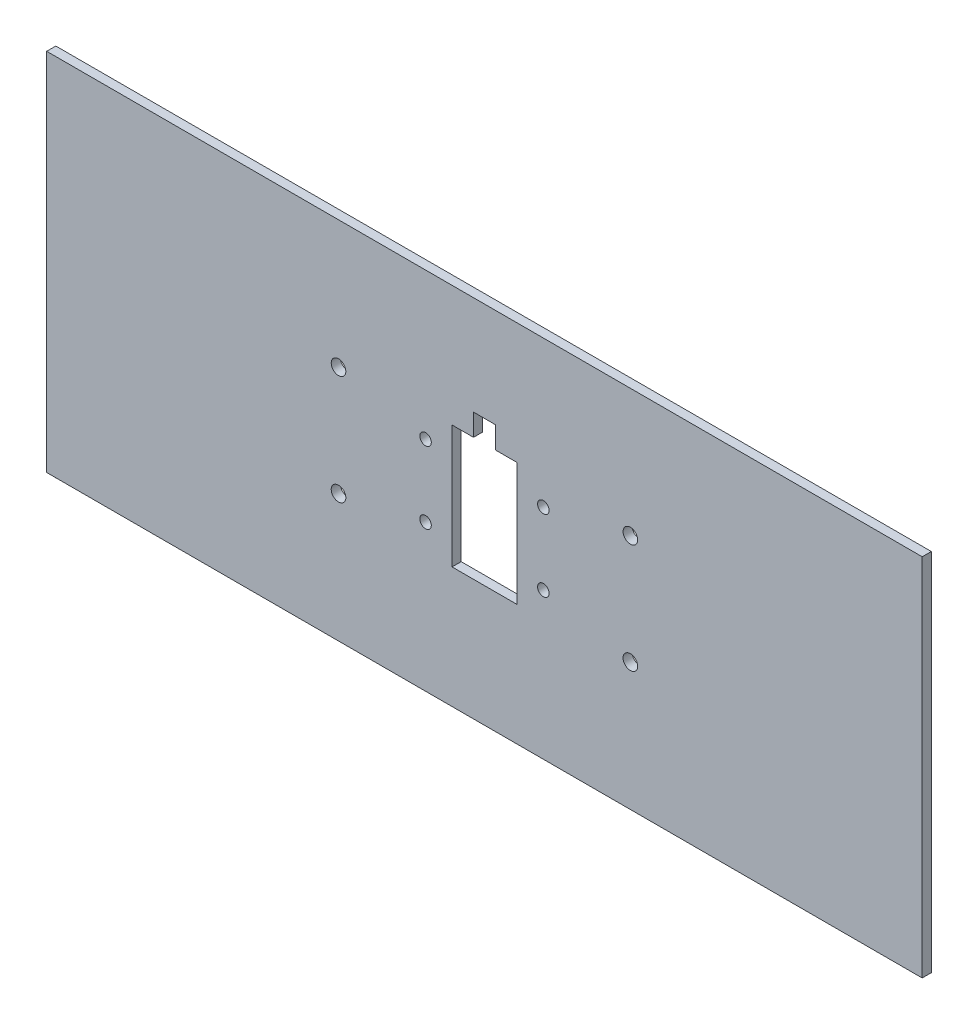
SolidWorks part; units mm, degrees
ref_plane "Front Plane" through (0, 0, 0) normal (0, 0, 1) x (1, 0, 0)
ref_plane "Top Plane" through (0, 0, 0) normal (0, 1, 0) x (1, 0, 0)
ref_plane "Right Plane" through (0, 0, 0) normal (1, 0, 0) x (0, 0, -1)
sketch "Sketch1" plane through (0, 0, 0) normal (0, 0, 1) x (1, 0, 0)
  line L0 (-152.4, 63.5) -> (152.4, -63.5) construction
  line L1 (-152.4, -63.5) -> (152.4, -63.5)
  line L2 (-152.4, -63.5) -> (-152.4, 63.5)
  line L3 (-152.4, 63.5) -> (152.4, 63.5)
  line L4 (152.4, -63.5) -> (152.4, 63.5)
  line L9 (-152.4, -63.5) -> (152.4, 63.5) construction
  point P4 (0, 0)
  dimension "D1" = 304.8
  dimension "D2" = 127
extrude "Boss-Extrude1" add sketch "Sketch1" along normal blind 3.175
sketch "Sketch2" plane through (0, 0, 3.175) normal (0, 0, 1) x (1, 0, 0)
  line L2 (50.8, 19.05) -> (-50.8, -19.05) construction
  line L3 (50.8, -19.05) -> (-50.8, 19.05) construction
  line L4 (50.8, 19.05) -> (-50.8, 19.05) construction
  line L5 (50.8, -19.05) -> (50.8, 19.05) construction
  circle A0 centre (50.8, 19.05) radius 2.54
  circle A1 centre (50.8, -19.05) radius 2.54
  circle A2 centre (-50.8, -19.05) radius 2.54
  circle A3 centre (-50.8, 19.05) radius 2.54
  point P6 (0, 0)
  dimension "D1" = 5.08
  dimension "D2" = 101.6
  dimension "D3" = 38.1
extrude "Cut-Extrude1" cut sketch "Sketch2" against normal through all
sketch "Sketch3" plane through (0, 0, 0) normal (0, 0, -1) x (-1, 0, 0)
  line L0 (11.27, 21.395) -> (11.27, -21.395)
  line L1 (10, 20.125) -> (10, -20.125) construction
  line L2 (10, 20.125) -> (-10, 20.125) construction
  line L3 (-10, 20.125) -> (-10, -20.125) construction
  line L4 (10, -20.125) -> (-10, -20.125) construction
  line L5 (11.27, -21.395) -> (-11.27, -21.395)
  line L6 (-11.27, 21.395) -> (-11.27, -21.395)
  line L7 (11.27, 21.395) -> (3.81, 21.395)
  line L9 (-3.81, 21.395) -> (-3.81, 29.015)
  line L11 (-3.81, 29.015) -> (3.81, 29.015)
  line L12 (3.81, 29.015) -> (3.81, 21.395)
  line L13 (0, 29.015) -> (0, 21.395) construction
  line L14 (-3.81, 21.395) -> (-11.27, 21.395)
  line L15 (11.27, 21.395) -> (-11.27, 21.395) construction
  line L16 (3.81, 21.395) -> (-3.81, 21.395) construction
  circle A0 centre (-20.5, 12.5) radius 2
  circle A1 centre (20.5, -12.5) radius 2
  circle A2 centre (20.5, 12.5) radius 2
  circle A3 centre (-20.5, -12.5) radius 2
  circle A5 centre (20.5, -12.5) radius 2 construction
  point P23 (0, 21.395)
  dimension "D2" = 7.62
  dimension "D3" = 7.62
  dimension "D1" = 1.27
extrude "Cut-Extrude2" cut sketch "Sketch3" against normal through all both and the other way through all
